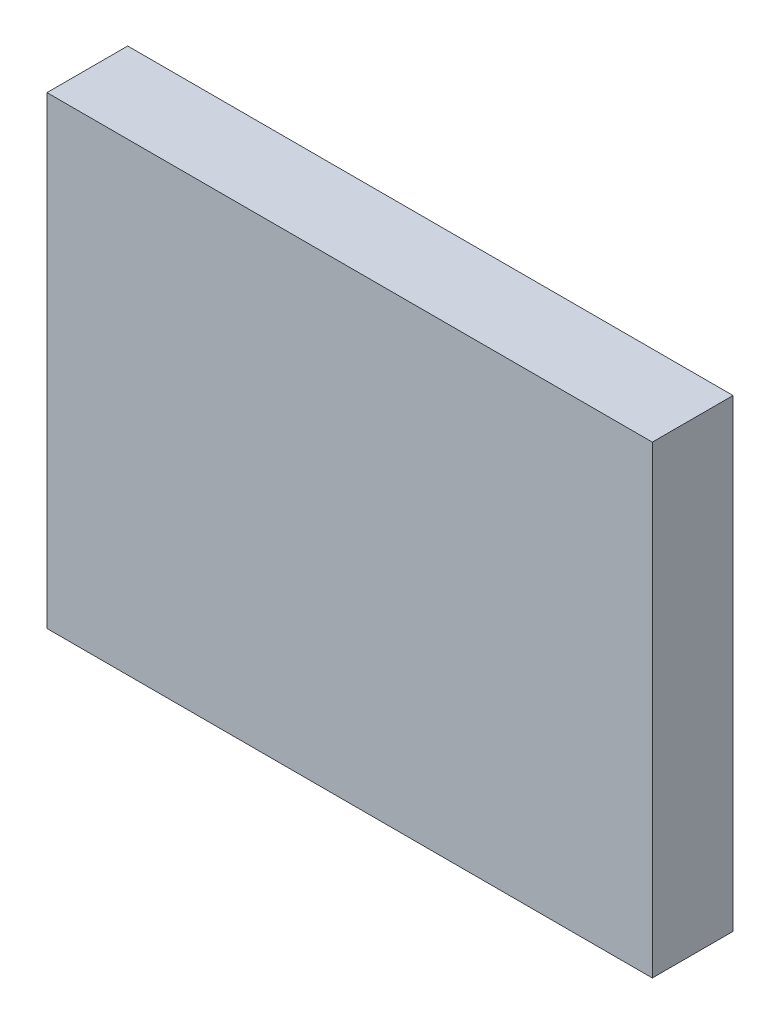
SolidWorks part; units mm, degrees
ref_plane "Plano frontal" through (0, 0, 0) normal (0, 0, 1) x (1, 0, 0)
ref_plane "Plano superior" through (0, 0, 0) normal (0, 1, 0) x (1, 0, 0)
ref_plane "Plano direito" through (0, 0, 0) normal (1, 0, 0) x (0, 0, -1)
sketch "Esboço1" plane through (0, 0, 0) normal (0, 0, 1) x (1, 0, 0)
  line L1 (-6.648, 5.6704) -> (8.352, 5.6704)
  line L2 (-6.648, 5.6704) -> (-6.648, -5.8296)
  line L3 (-6.648, -5.8296) -> (8.352, -5.8296)
  line L4 (8.352, 5.6704) -> (8.352, -5.8296)
  dimension "D1" = 15
  dimension "D2" = 11.5
extrude "Ressalto-extrusão1" add sketch "Esboço1" along normal blind 2
